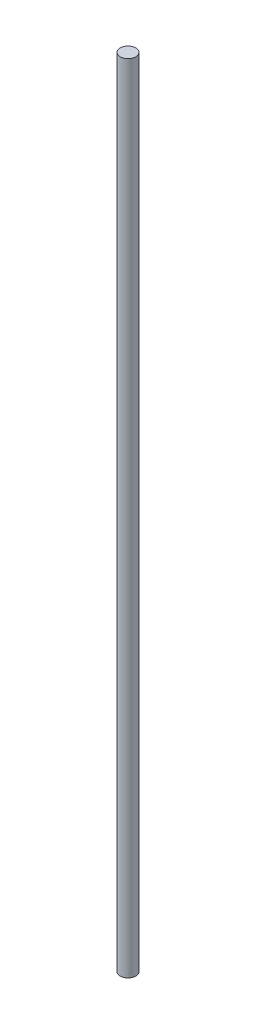
SolidWorks part; units mm, degrees
ref_plane "Front Plane" through (0, 0, 0) normal (0, 0, 1) x (1, 0, 0)
ref_plane "Top Plane" through (0, 0, 0) normal (0, 1, 0) x (1, 0, 0)
ref_plane "Right Plane" through (0, 0, 0) normal (1, 0, 0) x (0, 0, -1)
sketch "Sketch1" plane through (0, 0, 0) normal (0, 1, 0) x (1, 0, 0)
  circle A0 centre (0, 0) radius 2.413
  dimension "D1" = 4.826
extrude "Boss-Extrude1" add sketch "Sketch1" along normal blind 247.65
